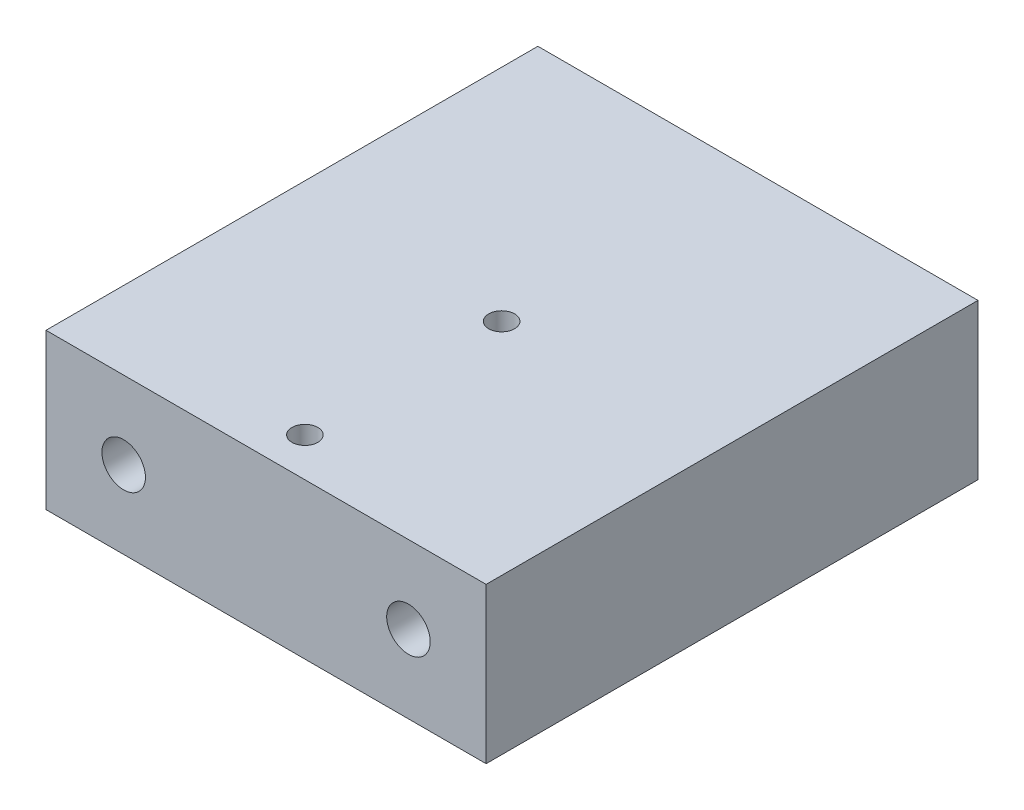
SolidWorks part; units mm, degrees
ref_plane "Ebene vorne" through (0, 0, 0) normal (0, 0, 1) x (1, 0, 0)
ref_plane "Ebene oben" through (0, 0, 0) normal (0, 1, 0) x (1, 0, 0)
ref_plane "Ebene rechts" through (0, 0, 0) normal (1, 0, 0) x (0, 0, -1)
sketch "Skizze1" plane through (0, 0, 0) normal (0, 0, 1) x (1, 0, 0)
  line L1 (0, 0) -> (42.5, 0)
  line L2 (0, 0) -> (0, 15)
  line L3 (0, 15) -> (42.5, 15)
  line L4 (42.5, 0) -> (42.5, 15)
  dimension "D1" = 42.5
  dimension "D2" = 15
extrude "Aufsatz-Linear austragen1" add sketch "Skizze1" along normal blind 47.5
hole_wizard "M5 Gewindebohrung1" positions "Skizze5" profile "Skizze4" tap size "M5" standard "DIN"
sketch "Skizze5" plane through (0, 0, 0) normal (0, 0, -1) x (-1, 0, 0)
  line L0 (-42.5, 15) -> (0, 15) construction
  line L1 (0, 15) -> (0, 0) construction
  line L2 (-42.5, 0) -> (-42.5, 15) construction
  point P0 (-7.5, 7.5)
  point P2 (-35, 7.5)
  dimension "D1" = 7.5
  dimension "D2" = 7.5
  dimension "D3" = 7.5
  dimension "D4" = 7.5
sketch "Skizze4" plane through (7.5, 7.5, 0) normal (1, 0, 0) x (0, 1, 0)
  line L0 (0, 0) -> (0, 11.2618)
  line L1 (0, 11.2618) -> (2.1, 10)
  line L2 (2.1, 10) -> (2.1, 0)
  line L5 (2.1, 0) -> (0, 0)
  line L10 (0, 11.2618) -> (-2.1, 10) construction
  line L11 (0, -6.35) -> (0, 107.95) construction
  dimension "Bohrerdurchmesser" = 4.2
  dimension "Bohrungstiefe" = 10
  dimension "Spitzenwinkel" = 118
cosmetic thread "Bohrungsgewinde1" parameters "D1"=10, "D2"=5
cosmetic thread "Bohrungsgewinde2" parameters "D1"=10, "D2"=5
hole_wizard "M5 Gewindebohrung2" positions "3D-Skizze1" profile "Skizze6" tap size "M5" standard "DIN"
sketch3d "3D-Skizze1"
  line L0 (0, 15, 47.5) -> (0, 0, 47.5) construction
  line L1 (42.5, 15, 47.5) -> (0, 15, 47.5) construction
  line L2 (42.5, 0, 47.5) -> (42.5, 15, 47.5) construction
  point P0 (7.5, 7.5, 47.5)
  point P2 (35, 7.5, 47.5)
  dimension "D1" = 7.5
  dimension "D2" = 7.5
  dimension "D3" = 7.5
  dimension "D4" = 7.5
sketch "Skizze6" plane through (7.5, 7.5, 47.5) normal (1, 0, 0) x (0, -1, 0)
  line L0 (0, 0) -> (0, 11.2618)
  line L1 (0, 11.2618) -> (2.1, 10)
  line L2 (2.1, 10) -> (2.1, 0)
  line L5 (2.1, 0) -> (0, 0)
  line L10 (0, 11.2618) -> (-2.1, 10) construction
  line L11 (0, -6.35) -> (0, 107.95) construction
  dimension "Bohrerdurchmesser" = 4.2
  dimension "Bohrungstiefe" = 10
  dimension "Spitzenwinkel" = 118
cosmetic thread "Bohrungsgewinde3"
cosmetic thread "Bohrungsgewinde4"
hole_wizard "M3 Gewindebohrung1" positions "3D-Skizze2" profile "Skizze7" tap size "M3" standard "DIN"
sketch3d "3D-Skizze2"
  line L0 (42.5, 15, 47.5) -> (42.5, 15, 0) construction
  line L1 (42.5, 15, 47.5) -> (0, 15, 47.5) construction
  point P0 (21.25, 15, 43.75)
  point P2 (21.25, 15, 24.75)
  dimension "D1" = 19
  dimension "D2" = 21.25
  dimension "D3" = 3.75
sketch "Skizze7" plane through (21.25, 15, 43.75) normal (1, 0, 0) x (0, 0, 1)
  line L0 (0, 0) -> (0, 9.2511)
  line L1 (0, 9.2511) -> (1.25, 8.5)
  line L2 (1.25, 8.5) -> (1.25, 0)
  line L5 (1.25, 0) -> (0, 0)
  line L10 (0, 9.2511) -> (-1.25, 8.5) construction
  line L11 (0, -6.35) -> (0, 107.95) construction
  dimension "Bohrerdurchmesser" = 2.5
  dimension "Bohrungstiefe" = 8.5
  dimension "Spitzenwinkel" = 118
cosmetic thread "Bohrungsgewinde5"
cosmetic thread "Bohrungsgewinde6"
